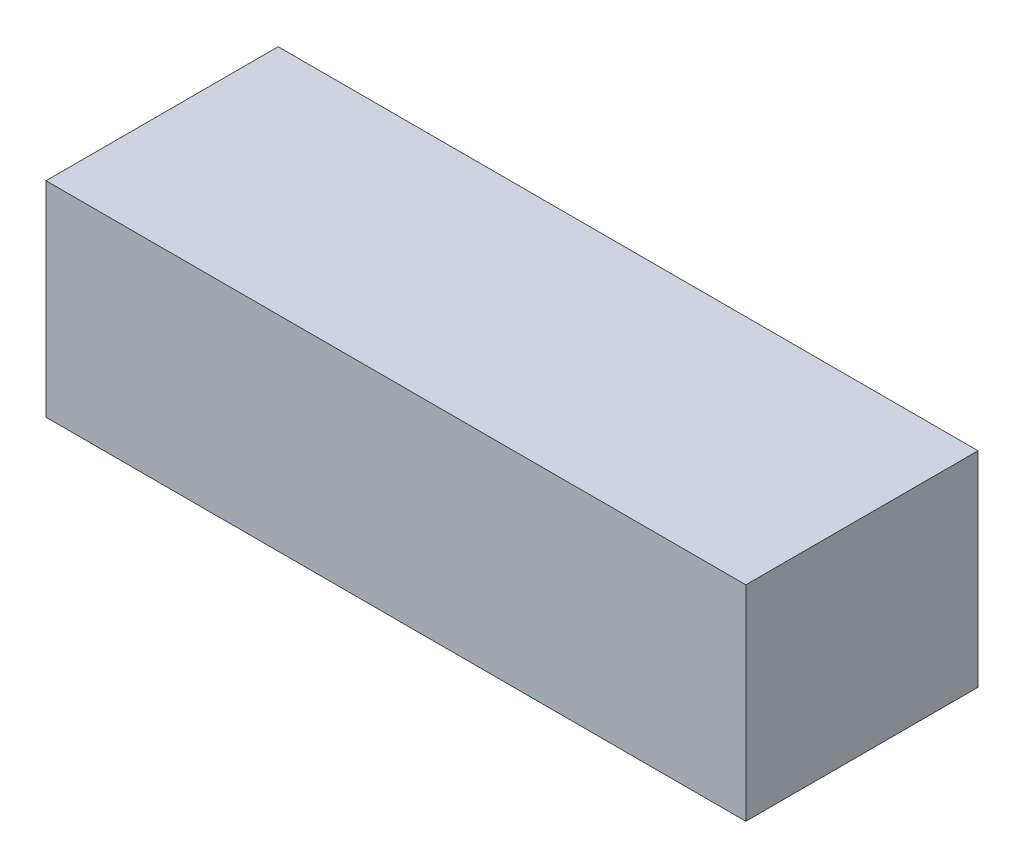
SolidWorks part; units mm, degrees
ref_plane "前视基准面" through (0, 0, 0) normal (0, 0, 1) x (1, 0, 0)
ref_plane "上视基准面" through (0, 0, 0) normal (0, 1, 0) x (1, 0, 0)
ref_plane "右视基准面" through (0, 0, 0) normal (1, 0, 0) x (0, 0, -1)
other "Configuration Table"
sketch "草图1" plane through (0, 0, 0) normal (0, 1, 0) x (1, 0, 0)
  line L1 (-51.25, -17) -> (51.25, -17)
  line L2 (-51.25, -17) -> (-51.25, 17)
  line L3 (-51.25, 17) -> (51.25, 17)
  line L4 (51.25, -17) -> (51.25, 17)
  line L5 (-51.25, -17) -> (51.25, 17) construction
  line L6 (-51.25, 17) -> (51.25, -17) construction
  point P0 (0, 0)
  dimension "D1" = 34
  dimension "D2" = 102.5
extrude "凸台-拉伸1" add sketch "草图1" along normal blind 30
